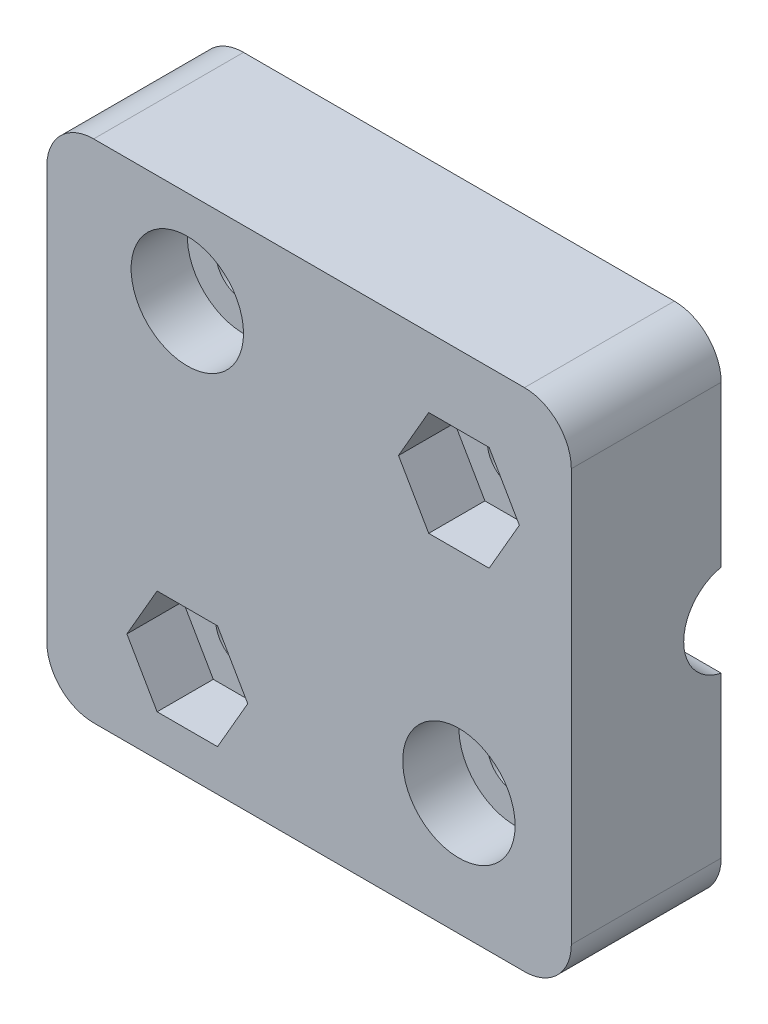
SolidWorks part; units mm, degrees
material "ABS"
ref_plane "Front Plane" through (0, 0, 0) normal (0, 0, 1) x (1, 0, 0)
ref_plane "Top Plane" through (0, 0, 0) normal (0, 1, 0) x (1, 0, 0)
ref_plane "Right Plane" through (0, 0, 0) normal (1, 0, 0) x (0, 0, -1)
sketch "Sketch1" plane through (0, 0, 0) normal (0, 0, 1) x (1, 0, 0)
  line L1 (14, 13.5) -> (-14, 13.5)
  line L2 (14, 13.5) -> (14, -13.5)
  line L3 (14, -13.5) -> (-14, -13.5)
  line L4 (-14, 13.5) -> (-14, -13.5)
  line L5 (14, 13.5) -> (-14, -13.5) construction
  line L6 (14, -13.5) -> (-14, 13.5) construction
  point P0 (0, 0)
  dimension "D1" = 28
  dimension "D2" = 27
extrude "Boss-Extrude1" add sketch "Sketch1" along normal blind 8
sketch "Sketch2" plane through (0, 0, 8) normal (0, 0, 1) x (1, 0, 0)
  line L0 (-6.5, 8.5) -> (-6.5, -8.5) construction
  line L1 (-6.5, 0) -> (-14, 0) construction
  line L2 (-14, 13.5) -> (-14, -13.5) construction
  line L3 (8, 7) -> (8, -7) construction
  line L4 (8, 0) -> (14, 0) construction
  line L5 (14, -13.5) -> (14, 13.5) construction
  circle A0 centre (-6.5, 8.5) radius 1.4837
  circle A1 centre (-6.5, -8.5) radius 1.4837
  circle A2 centre (8, -7) radius 1.4837
  circle A3 centre (8, 7) radius 1.4837
  dimension "D1" = 2.9674
  dimension "D4" = 6
  dimension "D2" = 14
  dimension "D3" = 17
  dimension "D5" = 7.5
extrude "Cut-Extrude1" cut sketch "Sketch2" against normal through all
sketch "Sketch3" plane through (0, 0, 8) normal (0, 0, 1) x (1, 0, 0)
  line L1 (-8.1127, -11.2933) -> (-4.8873, -11.2933)
  line L2 (-4.8873, -11.2933) -> (-3.2746, -8.5)
  line L3 (-3.2746, -8.5) -> (-4.8873, -5.7067)
  line L4 (-4.8873, -5.7067) -> (-8.1127, -5.7067)
  line L5 (-8.1127, -5.7067) -> (-9.7254, -8.5)
  line L6 (-9.7254, -8.5) -> (-8.1127, -11.2933)
  line L7 (6.3873, 4.2067) -> (9.6127, 4.2067)
  line L8 (9.6127, 4.2067) -> (11.2254, 7)
  line L9 (11.2254, 7) -> (9.6127, 9.7933)
  line L10 (9.6127, 9.7933) -> (6.3873, 9.7933)
  line L11 (6.3873, 9.7933) -> (4.7746, 7)
  line L12 (4.7746, 7) -> (6.3873, 4.2067)
  circle A0 centre (-6.5, 8.5) radius 3
  circle A1 centre (8, -7) radius 3
  circle A2 centre (-6.5, -8.5) radius 2.7933 construction
  circle A3 centre (8, 7) radius 2.7933 construction
  dimension "D1" = 6
  dimension "D2" = 5.5866
extrude "Cut-Extrude2" cut sketch "Sketch3" against normal blind 3
fillet "Fillet1" radius 2.5 4 edges at (14, 13.5, 4) (14, -13.5, 4) (-14, -13.5, 4) (-14, 13.5, 4)
sketch "Sketch4" plane through (14, 0, 0) normal (1, 0, 0) x (0, 0, -1)
  line L0 (0, 0) -> (0.5, 0) construction
  line L1 (0, -11) -> (0, 11) construction
  circle A0 centre (0.5, 0) radius 2.5
  dimension "D2" = 5
  dimension "D1" = 0.5
extrude "Cut-Extrude3" cut sketch "Sketch4" against normal blind 11.5
sketch "Sketch5" plane through (-14, 0, 0) normal (-1, 0, 0) x (0, 0, 1)
  line L0 (0, 11) -> (0, -11) construction
  circle A0 centre (-0.5, 0) radius 4
  dimension "D1" = 8
  dimension "D2" = 0.5
extrude "Cut-Extrude4" cut sketch "Sketch5" against normal blind 14
